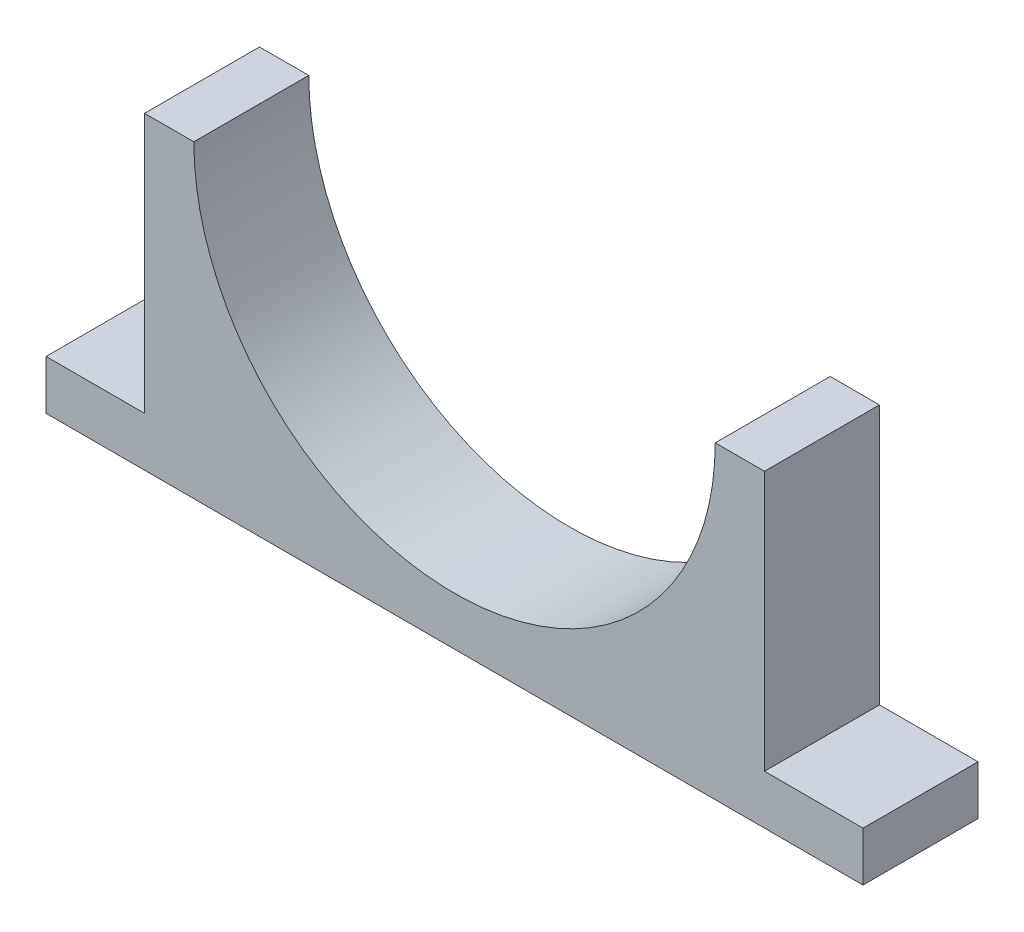
SolidWorks part; units mm, degrees
ref_plane "Front Plane" through (0, 0, 0) normal (0, 0, 1) x (1, 0, 0)
ref_plane "Top Plane" through (0, 0, 0) normal (0, 1, 0) x (1, 0, 0)
ref_plane "Right Plane" through (0, 0, 0) normal (1, 0, 0) x (0, 0, -1)
sketch "Sketch1" plane through (0, 0, 0) normal (0, 0, 1) x (1, 0, 0)
  line L0 (-15.875, 0) -> (-18.875, 0)
  line L1 (-18.875, 0) -> (-18.875, -15.82)
  line L2 (-18.875, -15.82) -> (-24.875, -15.82)
  line L3 (-24.875, -15.82) -> (-24.875, -18.82)
  line L4 (-24.875, -18.82) -> (24.875, -18.82)
  line L5 (24.875, -18.82) -> (24.875, -15.82)
  line L6 (24.875, -15.82) -> (18.875, -15.82)
  line L7 (18.875, -15.82) -> (18.875, 0)
  line L8 (18.875, 0) -> (15.875, 0)
  arc A0 (-15.875, 0) -> (15.875, 0) centre (0, 0) ccw
  dimension "D1" = 31.75
  dimension "D2" = 15.82
  dimension "D3" = 3
  dimension "D4" = 6
  dimension "D5" = 3
extrude "Boss-Extrude1" add sketch "Sketch1" along normal blind 7
